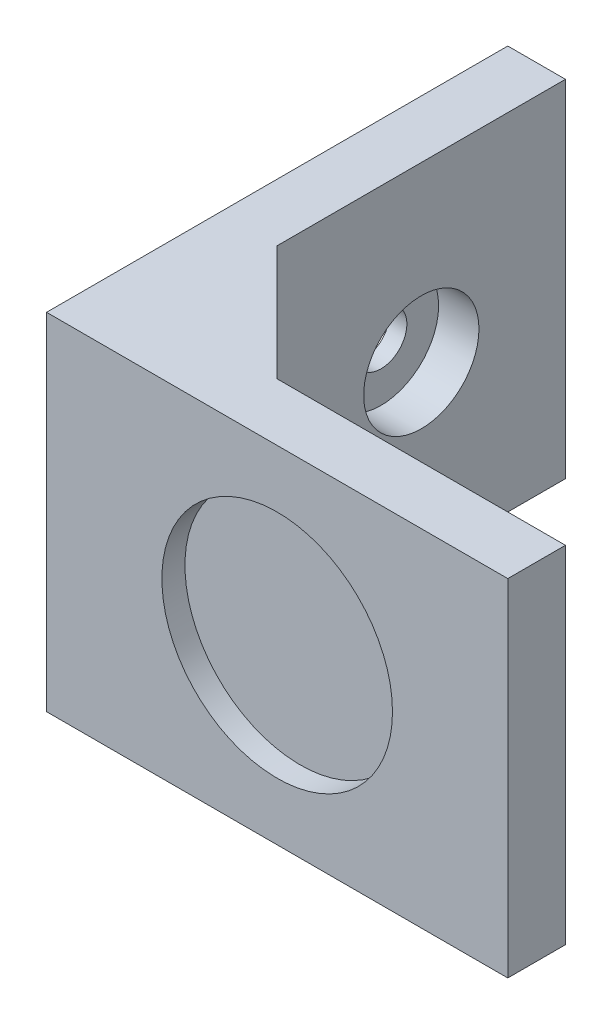
SolidWorks part; units mm, degrees
material "ABS generico"
ref_plane "Piano frontale" through (0, 0, 0) normal (0, 0, 1) x (1, 0, 0)
ref_plane "Piano superiore" through (0, 0, 0) normal (0, 1, 0) x (1, 0, 0)
ref_plane "Piano destro" through (0, 0, 0) normal (1, 0, 0) x (0, 0, -1)
sketch "Schizzo2" plane through (0, 0, 0) normal (0, 1, 0) x (1, 0, 0)
  line L0 (0, 25) -> (0, 0)
  line L1 (0, 0) -> (10, -10)
  line L2 (10, -10) -> (35, -10)
  line L3 (35, -10) -> (35, -15)
  line L4 (35, -15) -> (-5, -15)
  line L5 (-5, -15) -> (-5, 25)
  line L6 (-5, 25) -> (0, 25)
  dimension "D1" = 25
  dimension "D2" = 5
  dimension "D3" = 40
extrude "Estrusione-Estrusione2" add sketch "Schizzo2" along normal blind 30
sketch "Schizzo3" plane through (0, 0, 0) normal (1, 0, 0) x (0, 0, -1)
  line L0 (0, 0) -> (25, 0) construction
  line L1 (25, 30) -> (25, 0) construction
  point P0 (12.5, 15)
  dimension "D1" = 15
  dimension "D2" = 12.5
hole_wizard "Foro lamato per Vite M4 a testa cilindrica piana-1" positions "Schizzo3" profile "Schizzo5" counterbore size "M4" standard "ISO"
sketch "Schizzo5" plane through (0, 15, -12.5) normal (0, 1, 0) x (0, 0, -1)
  line L0 (0, 0) -> (0, 16.3519)
  line L1 (0, 16.3519) -> (2.25, 15)
  line L2 (2.25, 15) -> (2.25, 3.5)
  line L3 (2.25, 3.5) -> (5, 3.5)
  line L4 (5, 3.5) -> (5, 0)
  line L5 (5, 0) -> (0, 0)
  line L10 (0, 16.3519) -> (-2.25, 15) construction
  line L11 (0, -6.35) -> (0, 107.95) construction
  dimension "Hole Dia." = 4.5
  dimension "Hole Depth" = 15
  dimension "C'Bore Dia." = 10
  dimension "C'Bore Depth" = 3.5
  dimension "Drill Angle" = 118
sketch "Schizzo6" plane through (0, 0, 15) normal (0, 0, 1) x (1, 0, 0)
  line L0 (-5, 0) -> (35, 0) construction
  line L2 (35, 30) -> (35, 0) construction
  circle A0 centre (15, 15) radius 10
  dimension "D1" = 20
  dimension "D2" = 15
  dimension "D3" = 20
extrude "Taglio-Estrusione1" cut sketch "Schizzo6" against normal blind 2
